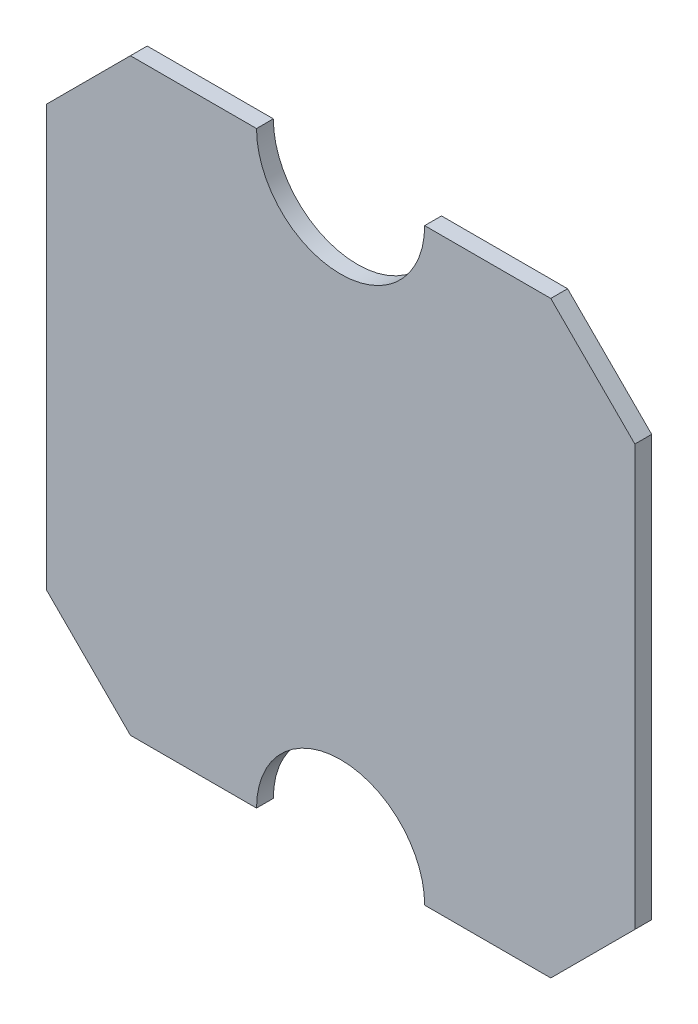
SolidWorks part; units mm, degrees
ref_plane "Front Plane" through (0, 0, 0) normal (0, 0, 1) x (1, 0, 0)
ref_plane "Top Plane" through (0, 0, 0) normal (0, 1, 0) x (1, 0, 0)
ref_plane "Right Plane" through (0, 0, 0) normal (1, 0, 0) x (0, 0, -1)
sketch "Sketch1" plane through (0, 0, 0) normal (0, 0, 1) x (1, 0, 0)
  line L0 (0, -175) -> (0, 175) construction
  line L1 (175, -175) -> (-175, -175)
  line L2 (175, -175) -> (175, 175)
  line L3 (175, 175) -> (-175, 175)
  line L4 (-175, -175) -> (-175, 175)
  line L5 (175, -175) -> (-175, 175) construction
  line L6 (175, 175) -> (-175, -175) construction
  line L7 (-175, 0) -> (175, 0) construction
  line L8 (-175, -125) -> (-125, -175)
  line L9 (175, -125) -> (125, -175)
  line L10 (175, 125) -> (125, 175)
  line L11 (-175, 125) -> (-125, 175)
  arc A0 (-50, -175) -> (50, -175) centre (0, -175) cw
  arc A1 (-50, 175) -> (50, 175) centre (0, 175) ccw
  point P0 (0, 0)
  dimension "D5" = 50
  dimension "D1" = 350
  dimension "D2" = 350
  dimension "D3" = 50
  dimension "D4" = 50
extrude "Boss-Extrude1" add sketch "Sketch1" along normal blind 10 contours A1 L3 L11 L4 L8 L1 A0 L9 L2 L10
